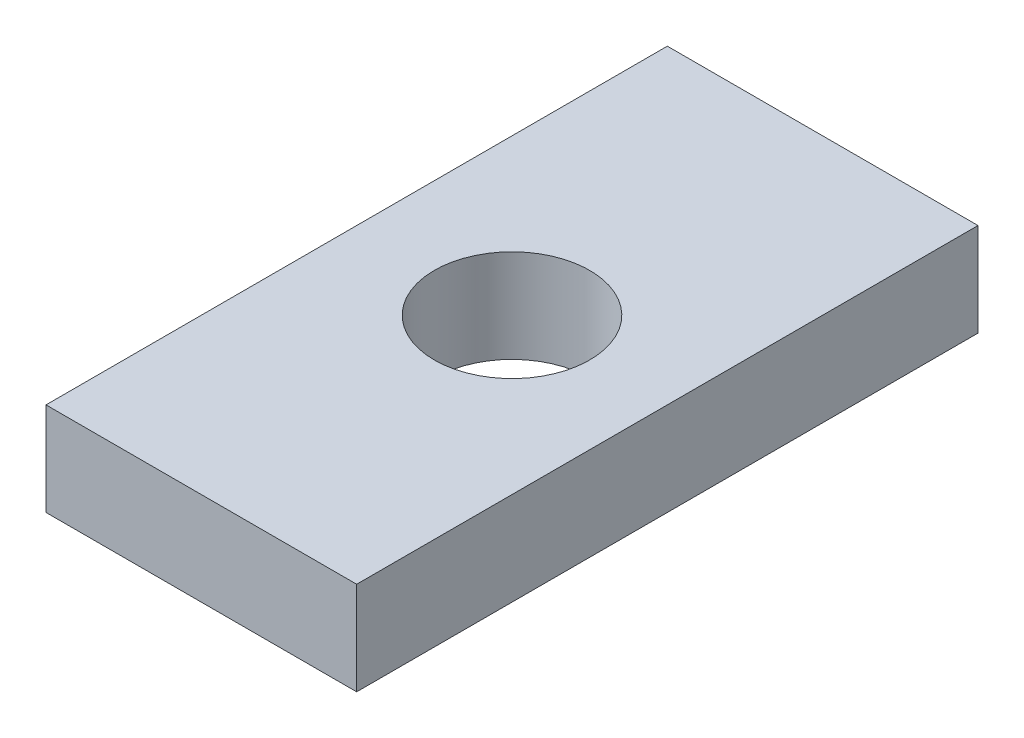
SolidWorks part; units mm, degrees
ref_plane "前基準面" through (0, 0, 0) normal (0, 0, 1) x (1, 0, 0)
ref_plane "上基準面" through (0, 0, 0) normal (0, 1, 0) x (1, 0, 0)
ref_plane "右基準面" through (0, 0, 0) normal (1, 0, 0) x (0, 0, -1)
sketch "草圖1" plane through (0, 0, 0) normal (0, 1, 0) x (1, 0, 0)
  line L1 (-10.9195, 6.6092) -> (-0.9195, 6.6092)
  line L2 (-10.9195, 6.6092) -> (-10.9195, -13.3908)
  line L3 (-10.9195, -13.3908) -> (-0.9195, -13.3908)
  line L4 (-0.9195, 6.6092) -> (-0.9195, -13.3908)
  circle A0 centre (-5.9195, -3.3908) radius 2.5
  dimension "D3" = 5
  dimension "D1" = 10
  dimension "D2" = 20
  dimension "D4" = 5
  dimension "D5" = 10
extrude "填料-伸長1" add sketch "草圖1" along normal blind 3
